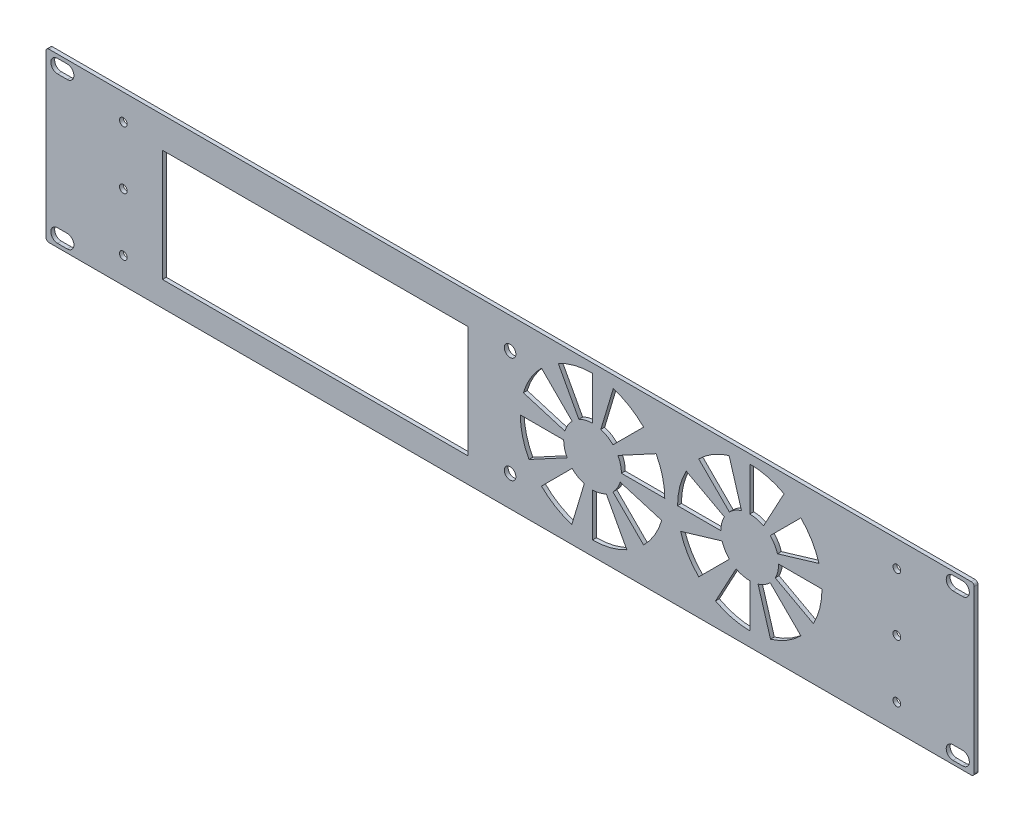
SolidWorks part; units mm, degrees
ref_plane "Ön Düzlem" through (0, 0, 0) normal (0, 0, 1) x (1, 0, 0)
ref_plane "Üst Düzlem" through (0, 0, 0) normal (0, 1, 0) x (1, 0, 0)
ref_plane "Sağ Düzlem" through (0, 0, 0) normal (1, 0, 0) x (0, 0, -1)
sketch "Sketch1" plane through (0, 0, 0) normal (0, 0, 1) x (1, 0, 0)
  line L0 (-235, 34.6) -> (-230, 34.6)
  line L1 (236, -43.5) -> (-236, -43.5)
  line L2 (241, -38.5) -> (241, 38.5)
  line L3 (236, 43.5) -> (-236, 43.5)
  line L4 (-241, -38.5) -> (-241, 38.5)
  line L5 (236, 43.5) -> (239.5, 43.5)
  line L6 (241, 42) -> (241, 38.5)
  line L7 (-235, 41.6) -> (-230, 41.6)
  line L8 (-241, 0) -> (-220.5012, 0) construction
  line L9 (-235, -41.6) -> (-230, -41.6)
  line L10 (-235, -34.6) -> (-230, -34.6)
  line L11 (0, 0) -> (0, -97.7221) construction
  line L12 (235, -41.6) -> (230, -41.6)
  line L13 (235, -34.6) -> (230, -34.6)
  line L14 (230, 41.6) -> (235, 41.6)
  line L15 (235, 34.6) -> (230, 34.6)
  line L16 (241, -38.5) -> (241, -42)
  line L17 (239.5, -43.5) -> (236, -43.5)
  line L18 (-236, -43.5) -> (-239.5, -43.5)
  line L19 (-241, -42) -> (-241, -38.5)
  line L20 (-241, 38.5) -> (-241, 42)
  line L21 (-239.5, 43.5) -> (-236, 43.5)
  line L22 (0, 0) -> (19.053, 0) construction
  circle A4 centre (-200.85, 30) radius 2
  circle A5 centre (-200.85, 0) radius 2
  circle A6 centre (-200.85, -30) radius 2
  circle A7 centre (200.85, 30) radius 2
  circle A8 centre (200.85, 0) radius 2
  circle A9 centre (200.85, -30) radius 2
  arc A10 (-230, 34.6) -> (-230, 41.6) centre (-230, 38.1) ccw
  arc A11 (-235, 41.6) -> (-235, 34.6) centre (-235, 38.1) ccw
  arc A12 (-235, -41.6) -> (-235, -34.6) centre (-235, -38.1) cw
  arc A13 (-230, -34.6) -> (-230, -41.6) centre (-230, -38.1) cw
  arc A14 (230, -34.6) -> (230, -41.6) centre (230, -38.1) ccw
  arc A15 (235, -41.6) -> (235, -34.6) centre (235, -38.1) ccw
  arc A16 (235, 41.6) -> (235, 34.6) centre (235, 38.1) cw
  arc A17 (230, 34.6) -> (230, 41.6) centre (230, 38.1) cw
  arc A18 (239.5, 43.5) -> (241, 42) centre (239.5, 42) cw
  arc A19 (241, -42) -> (239.5, -43.5) centre (239.5, -42) cw
  arc A20 (-239.5, -43.5) -> (-241, -42) centre (-239.5, -42) cw
  arc A21 (-241, 42) -> (-239.5, 43.5) centre (-239.5, 42) cw
  circle A22 centre (0, -27.56) radius 3
  circle A23 centre (0, 27.56) radius 3
  point P0 (0, 0)
  point P72 (241, -43.5)
  point P78 (0, 0)
  dimension "D1" = 55.12
  dimension "D2" = 6
extrude "Boss-Extrude1" add sketch "Sketch1" along normal blind 2
sketch "Sketch2" plane through (0, 0, 2) normal (0, 0, 1) x (1, 0, 0)
  line L0 (124.4886, 16.4094) -> (124.4886, 38.9094)
  line L1 (131.6081, 14.6122) -> (142.2873, 34.4163)
  line L2 (138.8586, 5.711) -> (160.4136, 12.1632)
  line L3 (135.0952, 12.016) -> (151.0051, 27.9259)
  line L4 (137.6913, -5.7101) -> (157.4954, -16.3893)
  line L5 (139.4886, 1.4094) -> (161.9886, 1.4094)
  line L6 (128.7901, -12.9606) -> (135.2423, -34.5156)
  line L7 (135.0952, -9.1972) -> (151.0051, -25.1071)
  line L8 (117.369, -11.7933) -> (106.6898, -31.5974)
  line L9 (124.4886, -13.5906) -> (124.4886, -36.0906)
  line L10 (110.1185, -2.8921) -> (88.5635, -9.3443)
  line L11 (113.8819, -9.1972) -> (97.972, -25.1071)
  line L12 (111.2858, 8.5289) -> (91.4817, 19.2082)
  line L13 (109.4886, 1.4094) -> (86.9886, 1.4094)
  line L14 (120.187, 15.7794) -> (113.7348, 37.3345)
  line L15 (113.8819, 12.016) -> (97.972, 27.9259)
  line L16 (124.4886, 1.4094) -> (42.8267, 1.6386) construction
  line L17 (83.6576, 1.524) -> (83.6576, 61.116) construction
  line L18 (53.4333, 12.016) -> (69.3432, 27.9259)
  line L19 (47.1282, 15.7794) -> (53.5805, 37.3345)
  line L20 (57.8267, 1.4094) -> (80.3267, 1.4094)
  line L21 (56.0295, 8.5289) -> (75.8336, 19.2082)
  line L22 (53.4333, -9.1972) -> (69.3432, -25.1071)
  line L23 (57.1967, -2.8921) -> (78.7517, -9.3443)
  line L24 (42.8267, -13.5906) -> (42.8267, -36.0906)
  line L25 (49.9462, -11.7933) -> (60.6255, -31.5974)
  line L26 (32.2201, -9.1972) -> (16.3102, -25.1071)
  line L27 (38.5252, -12.9606) -> (32.073, -34.5156)
  line L28 (27.8267, 1.4094) -> (5.3267, 1.4094)
  line L29 (29.624, -5.7101) -> (9.8198, -16.3893)
  line L30 (32.2201, 12.016) -> (16.3102, 27.9259)
  line L31 (28.4567, 5.711) -> (6.9017, 12.1632)
  line L32 (35.7072, 14.6122) -> (25.028, 34.4163)
  line L33 (42.8267, 16.4094) -> (42.8267, 38.9094)
  circle A0 centre (124.4886, 1.4094) radius 37.5 construction
  arc A1 (124.4886, 38.9094) -> (142.2873, 34.4163) centre (124.4886, 1.4094) cw
  arc A2 (124.4886, 16.4094) -> (131.6081, 14.6122) centre (124.4886, 1.4094) cw
  arc A3 (128.0132, 15.9895) -> (115.2654, 13.2388) centre (124.4886, 1.4094) ccw construction
  circle A4 centre (124.4886, 1.4094) radius 15 construction
  arc A5 (151.0051, 27.9259) -> (160.4136, 12.1632) centre (124.4886, 1.4094) cw
  arc A6 (135.0952, 12.016) -> (138.8586, 5.711) centre (124.4886, 1.4094) cw
  arc A7 (161.9886, 1.4094) -> (157.4954, -16.3893) centre (124.4886, 1.4094) cw
  arc A8 (139.4886, 1.4094) -> (137.6913, -5.7101) centre (124.4886, 1.4094) cw
  arc A9 (151.0051, -25.1071) -> (135.2423, -34.5156) centre (124.4886, 1.4094) cw
  arc A10 (135.0952, -9.1972) -> (128.7901, -12.9606) centre (124.4886, 1.4094) cw
  arc A11 (124.4886, -36.0906) -> (106.6898, -31.5974) centre (124.4886, 1.4094) cw
  arc A12 (124.4886, -13.5906) -> (117.369, -11.7933) centre (124.4886, 1.4094) cw
  arc A13 (97.972, -25.1071) -> (88.5635, -9.3443) centre (124.4886, 1.4094) cw
  arc A14 (113.8819, -9.1972) -> (110.1185, -2.8921) centre (124.4886, 1.4094) cw
  arc A15 (86.9886, 1.4094) -> (91.4817, 19.2082) centre (124.4886, 1.4094) cw
  arc A16 (109.4886, 1.4094) -> (111.2858, 8.5289) centre (124.4886, 1.4094) cw
  arc A17 (97.972, 27.9259) -> (113.7348, 37.3345) centre (124.4886, 1.4094) cw
  arc A18 (113.8819, 12.016) -> (120.187, 15.7794) centre (124.4886, 1.4094) cw
  arc A19 (53.4333, 12.016) -> (47.1282, 15.7794) centre (42.8267, 1.4094) ccw
  arc A20 (69.3432, 27.9259) -> (53.5805, 37.3345) centre (42.8267, 1.4094) ccw
  arc A21 (57.8267, 1.4094) -> (56.0295, 8.5289) centre (42.8267, 1.4094) ccw
  arc A22 (80.3267, 1.4094) -> (75.8336, 19.2082) centre (42.8267, 1.4094) ccw
  arc A23 (53.4333, -9.1972) -> (57.1967, -2.8921) centre (42.8267, 1.4094) ccw
  arc A24 (69.3432, -25.1071) -> (78.7517, -9.3443) centre (42.8267, 1.4094) ccw
  arc A25 (42.8267, -13.5906) -> (49.9462, -11.7933) centre (42.8267, 1.4094) ccw
  arc A26 (42.8267, -36.0906) -> (60.6255, -31.5974) centre (42.8267, 1.4094) ccw
  arc A27 (32.2201, -9.1972) -> (38.5252, -12.9606) centre (42.8267, 1.4094) ccw
  arc A28 (16.3102, -25.1071) -> (32.073, -34.5156) centre (42.8267, 1.4094) ccw
  arc A29 (27.8267, 1.4094) -> (29.624, -5.7101) centre (42.8267, 1.4094) ccw
  arc A30 (5.3267, 1.4094) -> (9.8198, -16.3893) centre (42.8267, 1.4094) ccw
  arc A31 (32.2201, 12.016) -> (28.4567, 5.711) centre (42.8267, 1.4094) ccw
  arc A32 (16.3102, 27.9259) -> (6.9017, 12.1632) centre (42.8267, 1.4094) ccw
  arc A33 (42.8267, 16.4094) -> (35.7072, 14.6122) centre (42.8267, 1.4094) ccw
  arc A34 (42.8267, 38.9094) -> (25.028, 34.4163) centre (42.8267, 1.4094) ccw
  point P44 (124.4886, 1.4094)
  point P80 (42.8267, 1.4094)
  dimension "D1" = 8
extrude "Cut-Extrude1" cut sketch "Sketch2" against normal blind 3
sketch "Sketch3" plane through (0, 0, 2) normal (0, 0, 1) x (1, 0, 0)
  line L1 (-180.4883, 27.5216) -> (-21.8568, 27.5216)
  line L2 (-180.4883, 27.5216) -> (-180.4883, -30.6051)
  line L3 (-180.4883, -30.6051) -> (-21.8568, -30.6051)
  line L4 (-21.8568, 27.5216) -> (-21.8568, -30.6051)
extrude "Cut-Extrude2" cut sketch "Sketch3" against normal blind 3
